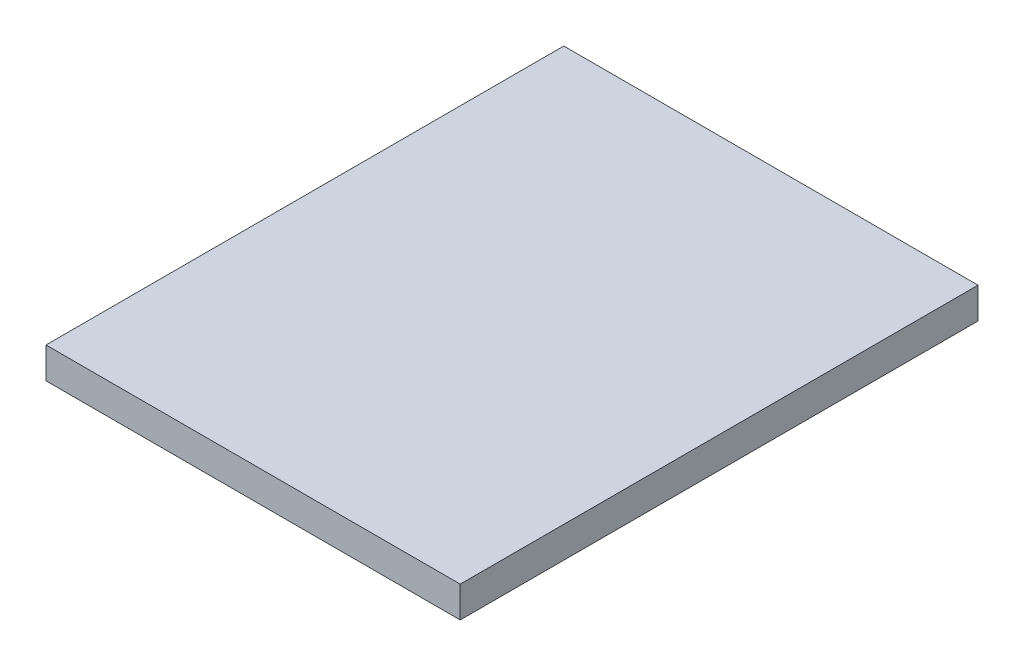
SolidWorks part; units mm, degrees
ref_plane "Front Plane" through (0, 0, 0) normal (0, 0, 1) x (1, 0, 0)
ref_plane "Top Plane" through (0, 0, 0) normal (0, 1, 0) x (1, 0, 0)
ref_plane "Right Plane" through (0, 0, 0) normal (1, 0, 0) x (0, 0, -1)
sketch "Sketch1" plane through (0, 0, 0) normal (0, 1, 0) x (1, 0, 0)
  line L1 (0, 0) -> (40, 0)
  line L2 (0, 0) -> (0, 50)
  line L3 (0, 50) -> (40, 50)
  line L4 (40, 0) -> (40, 50)
  dimension "D1" = 50
  dimension "D2" = 40
extrude "Boss-Extrude1" add sketch "Sketch1" along normal blind 3
